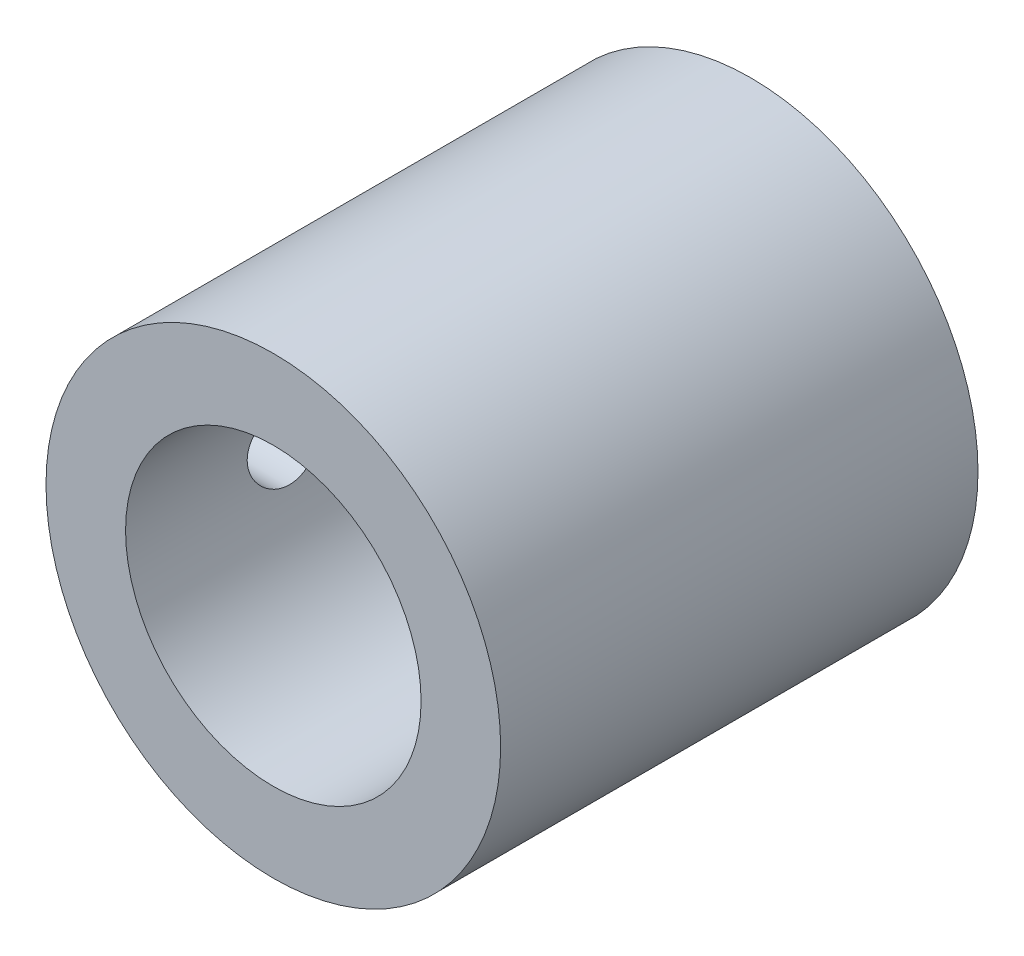
SolidWorks part; units mm, degrees
material "3.1355 (EN-AW 2024)"
ref_plane "Front" through (0, 0, 0) normal (0, 0, 1) x (1, 0, 0)
ref_plane "Top" through (0, 0, 0) normal (0, 1, 0) x (1, 0, 0)
ref_plane "Right" through (0, 0, 0) normal (1, 0, 0) x (0, 0, -1)
sketch "Эскиз1" plane through (0, 0, 0) normal (0, 0, 1) x (1, 0, 0)
  circle A0 centre (0, 0) radius 10
  dimension "D1" = 20
extrude "Бобышка-Вытянуть1" add sketch "Эскиз1" along normal blind 21
sketch "Эскиз2" plane through (0, 0, 21) normal (0, 0, 1) x (1, 0, 0)
  circle A0 centre (0, 0) radius 6.5
  dimension "D1" = 13
extrude "Вырез-Вытянуть1" cut sketch "Эскиз2" against normal blind 15
sketch "Эскиз3" plane through (0, 0, 0) normal (0, 1, 0) x (1, 0, 0)
  line L0 (-10, -21) -> (-10, -16) construction
  dimension "D1" = 5
ref_plane "Плоскость1" through (-10, 0, 0) normal (1, 0, 0) x (0, 0, -1)
hole_wizard "Отверстие обработанное метчиком M4x0.71" positions "Эскиз5" profile "Эскиз4" tap size "M4x0.7" standard "Ansi Metric"
sketch "Эскиз5" plane through (-10, 0, 0) normal (1, 0, 0) x (0, 0, -1)
  line L0 (-21, 0) -> (-16, 0) construction
  point P0 (-14, 0)
sketch "Эскиз4" plane through (-10, 0, 14) normal (0, 1, 0) x (0, 0, 1)
  line L0 (0, 0) -> (0, 5.9914)
  line L1 (0, 5.9914) -> (1.65, 5)
  line L2 (1.65, 5) -> (1.65, 0)
  line L5 (1.65, 0) -> (0, 0)
  line L10 (0, 5.9914) -> (-1.65, 5) construction
  line L11 (0, -6.35) -> (0, 107.95) construction
  dimension "Диаметр сверла" = 3.3
  dimension "Глубина сверла" = 5
  dimension "Угол заточки сверла" = 118
cosmetic thread "Отверстие резьбы1" parameters "D1"=3.7129, "D2"=4
sketch "Эскиз7" plane through (0, 0, 0) normal (0, 0, -1) x (-1, 0, 0)
  line L0 (-6, 0) -> (0, 0) construction
  line L1 (0, 0) -> (-4.2426, 4.2426) construction
  line L2 (0, 0) -> (4.2426, 4.2426) construction
  line L3 (0, 0) -> (4.2426, -4.2426) construction
  line L4 (0, 0) -> (-4.2426, -4.2426) construction
  circle A0 centre (0, 0) radius 6 construction
  point P11 (0, 0)
  dimension "D1" = 12
  dimension "D2" = 45
  dimension "D3" = 4
hole_wizard "Отверстие обработанное метчиком M3x0.51" positions "Эскиз9" profile "Эскиз8" tap size "M3x0.5" standard "Ansi Metric"
sketch "Эскиз9" plane through (0, 0, 0) normal (0, 0, -1) x (-1, 0, 0)
  point P0 (-4.2426, 4.2426)
  point P3 (4.2426, 4.2426)
  point P6 (4.2426, -4.2426)
  point P9 (-4.2426, -4.2426)
sketch "Эскиз8" plane through (4.2426, 4.2426, 0) normal (1, 0, 0) x (0, 1, 0)
  line L0 (0, 0) -> (0, 6)
  line L1 (0, 6) -> (1.25, 6)
  line L2 (1.25, 6) -> (1.25, 0)
  line L5 (1.25, 0) -> (0, 0)
  line L11 (0, -6.35) -> (0, 107.95) construction
  dimension "Диаметр проходного сверла" = 2.5
  dimension "Глубина проходного сверла" = 6
cosmetic thread "Отверстие резьбы2" parameters "D2"=3
cosmetic thread "Отверстие резьбы3" parameters "D2"=3
cosmetic thread "Отверстие резьбы4" parameters "D2"=3
cosmetic thread "Отверстие резьбы5" parameters "D2"=3
hole_wizard "Цековка для  винта с полукруглой головкой M31" positions "Эскиз11" profile "Эскиз10" counterbore size "M3" standard "Ansi Metric" end condition through all
sketch "Эскиз11" plane through (0, 0, 0) normal (0, 0, -1) x (-1, 0, 0)
  point P0 (0, 0)
sketch "Эскиз10" plane through (0, 0, 0) normal (1, 0, 0) x (0, 1, 0)
  line L0 (0, 0) -> (0, 21)
  line L1 (0, 21) -> (1.7, 21)
  line L3 (1.7, 21) -> (1.7, 1.8)
  line L4 (1.7, 1.8) -> (3.35, 1.8)
  line L5 (3.35, 1.8) -> (3.35, 0)
  line L7 (3.35, 0) -> (0, 0)
  line L11 (0, -6.35) -> (0, 107.95) construction
  dimension "Диаметр сквозного отверстия" = 3.4
  dimension "Глубина сквозного отверстия" = 21
  dimension "Диаметр цековки" = 6.7
  dimension "Глубина цековки" = 1.8
